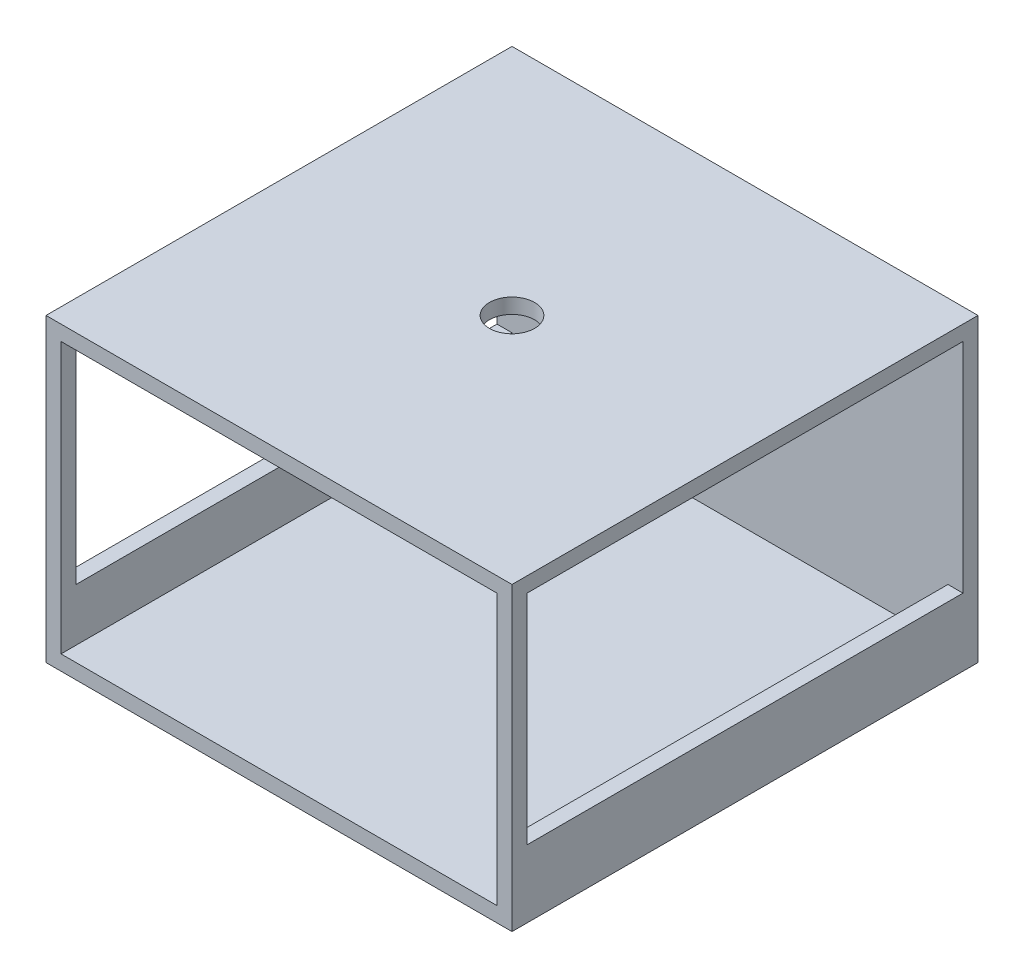
SolidWorks part; units mm, degrees
other "Markup1"
sketch "Sketch4" plane through (-75, 100, 75) normal (-0.3285, 0.0271, 0.9441) x (0.9445, 0.0024, 0.3286)
ref_plane "Front Plane" through (0, 0, 0) normal (0, 0, 1) x (1, 0, 0)
ref_plane "Top Plane" through (0, 0, 0) normal (0, 1, 0) x (1, 0, 0)
ref_plane "Right Plane" through (0, 0, 0) normal (1, 0, 0) x (0, 0, -1)
sketch "Sketch1" plane through (0, 0, 0) normal (0, 1, 0) x (1, 0, 0)
  line L1 (-77.5, -77.5) -> (77.5, -77.5)
  line L2 (-77.5, -77.5) -> (-77.5, 77.5)
  line L3 (-77.5, 77.5) -> (77.5, 77.5)
  line L4 (77.5, -77.5) -> (77.5, 77.5)
  line L5 (-77.5, -77.5) -> (77.5, 77.5) construction
  line L6 (-77.5, 77.5) -> (77.5, -77.5) construction
  point P0 (0, 0)
  dimension "D1" = 155
  dimension "D2" = 155
extrude "Boss-Extrude1" add sketch "Sketch1" along normal blind 100
shell "Shell1" thickness 5
sketch "Sketch2" plane through (0, 100, 0) normal (0, 1, 0) x (1, 0, 0)
  circle A0 centre (0, 0) radius 7.5
  dimension "D1" = 15
extrude "Cut-Extrude1" cut sketch "Sketch2" against normal blind 5
sketch "Sketch5" plane through (-77.5, 0, 0) normal (-1, 0, 0) x (0, 0, 1)
  line L0 (-77.5, 100) -> (-77.5, 0) construction
  line L1 (-72.5, 95) -> (72.5, 95)
  line L2 (-72.5, 95) -> (-72.5, 22.5)
  line L3 (-72.5, 22.5) -> (72.5, 22.5)
  line L4 (72.5, 95) -> (72.5, 22.5)
  line L5 (-77.5, 100) -> (77.5, 100) construction
  line L6 (77.5, 100) -> (77.5, 0) construction
  line L7 (-77.5, 0) -> (77.5, 0) construction
  dimension "D1" = 5
  dimension "D2" = 5
  dimension "D3" = 5
  dimension "D4" = 22.5
extrude "Cut-Extrude2" cut sketch "Sketch5" against normal up to surface (155 mm away) up to face at (77.5, 50, 0)
